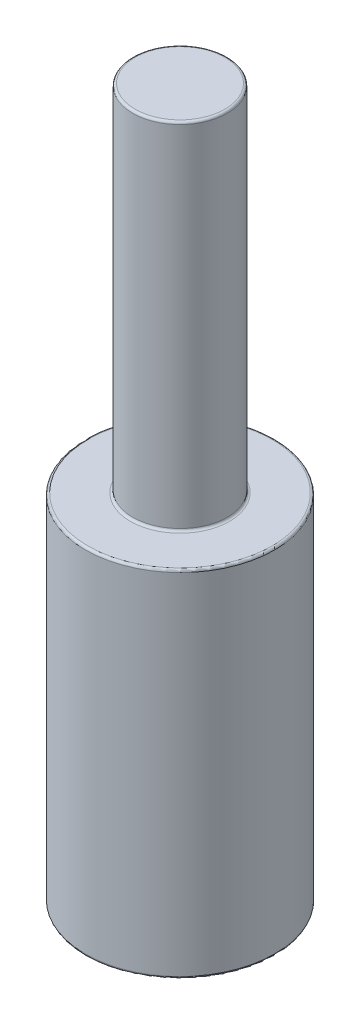
SolidWorks part; units mm, degrees
ref_plane "Спереди" through (0, 0, 0) normal (0, 0, 1) x (1, 0, 0)
ref_plane "Сверху" through (0, 0, 0) normal (0, 1, 0) x (1, 0, 0)
ref_plane "Справа" through (0, 0, 0) normal (1, 0, 0) x (0, 0, -1)
sketch "Эскиз1" plane through (0, 0, 0) normal (0, 1, 0) x (1, 0, 0)
  circle A0 centre (0, 0) radius 40
extrude "Бобышка-Вытянуть1" add sketch "Эскиз1" along normal blind 300
sketch "Эскиз2" plane through (0, 300, 0) normal (0, 1, 0) x (1, 0, 0)
  circle A0 centre (0, 0) radius 20
extrude "Вырез-Вытянуть1" cut sketch "Эскиз2" against normal blind 150 flip side to cut contours A0
fillet "Скругление2" radius 1 1 edges at (0, 150, 20)
fillet "Скругление3" radius 1 1 edges at (0, 300, 20)
fillet "Скругление4" radius 1 1 edges at (0, 0, 40)
fillet "Скругление5" radius 1 1 edges at (0, 150, 40)
